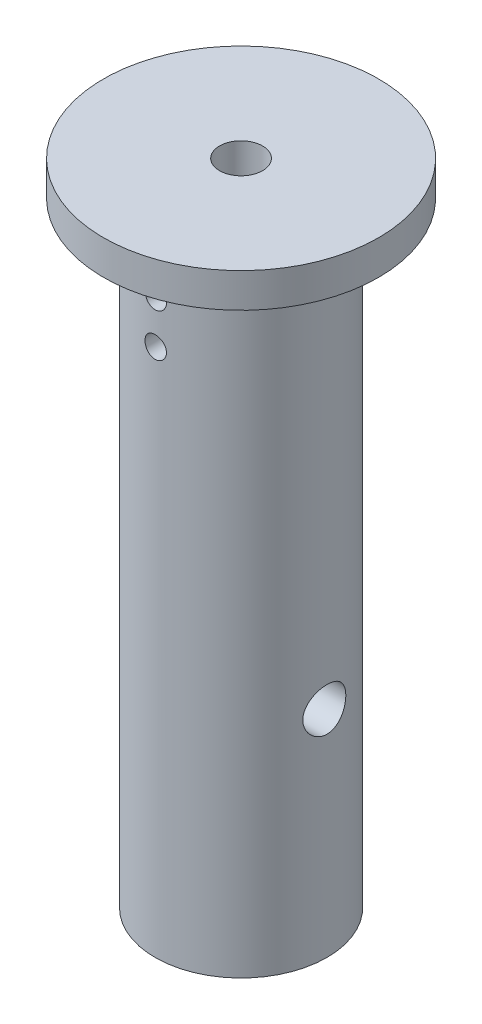
SolidWorks part; units mm, degrees
ref_plane "Front Plane" through (0, 0, 0) normal (0, 0, 1) x (1, 0, 0)
ref_plane "Top Plane" through (0, 0, 0) normal (0, 1, 0) x (1, 0, 0)
ref_plane "Right Plane" through (0, 0, 0) normal (1, 0, 0) x (0, 0, -1)
sketch "Sketch1" plane through (0, 0, 0) normal (0, 0, 1) x (1, 0, 0)
  line L0 (0, -45.5) -> (0, 42.4375) construction
  line L1 (2.5, 30) -> (2.5, 0)
  line L2 (2.5, 0) -> (0, 0)
  line L3 (0, 0) -> (0, -45.5)
  line L4 (0, -45.5) -> (10, -45.5)
  line L9 (10, -45.5) -> (10, 26)
  line L10 (10, 26) -> (16, 26)
  line L11 (16, 26) -> (16, 30)
  line L12 (16, 30) -> (2.5, 30)
  dimension "D1" = 30
  dimension "D3" = 32
  dimension "D4" = 5
  dimension "D5" = 20
  dimension "D6" = 4
  dimension "D7" = 75.5
revolve "Revolve1" add sketch "Sketch1" angle 360 about L0
hole_wizard "M3 Tapped Hole2" positions "Sketch2" profile "Sketch3" tap size "M3" standard "ISO"
sketch "Sketch2" plane through (0, -45.5, 0) normal (0, -1, 0) x (-1, 0, 0)
  line L1 (-3.5355, -3.5355) -> (3.5355, -3.5355)
  line L2 (-3.5355, -3.5355) -> (-3.5355, 3.5355)
  line L3 (-3.5355, 3.5355) -> (3.5355, 3.5355)
  line L4 (3.5355, -3.5355) -> (3.5355, 3.5355)
  line L5 (-3.5355, -3.5355) -> (3.5355, 3.5355) construction
  line L6 (-3.5355, 3.5355) -> (3.5355, -3.5355) construction
  line L7 (0, 0) -> (7.0711, -7.0711) construction
  circle A0 centre (0, 0) radius 10 construction
  point P0 (-3.5355, 3.5355)
  point P392 (-3.5355, -3.5355)
  point P395 (3.5355, -3.5355)
  point P398 (3.5355, 3.5355)
sketch "Sketch3" plane through (3.5355, -45.5, -3.5355) normal (1, 0, 0) x (0, 0, -1)
  line L0 (0, 0) -> (0, 8.2511)
  line L1 (0, 8.2511) -> (1.25, 7.5)
  line L2 (1.25, 7.5) -> (1.25, 0)
  line L5 (1.25, 0) -> (0, 0)
  line L10 (0, 8.2511) -> (-1.25, 7.5) construction
  line L11 (0, -6.35) -> (0, 107.95) construction
  dimension "Tap Drill Dia." = 2.5
  dimension "Tap Drill Depth" = 7.5
  dimension "Drill Angle" = 118
cosmetic thread "Hole Thread1" parameters "D1"=6, "D2"=3
cosmetic thread "Hole Thread4" parameters "D1"=6, "D2"=3
cosmetic thread "Hole Thread5" parameters "D1"=6, "D2"=3
cosmetic thread "Hole Thread6" parameters "D1"=6, "D2"=3
ref_plane "Plane1" through (-10, 0, 0) normal (-1, 0, 0) x (0, 0, 1)
sketch "Sketch4" plane through (-10, 0, 0) normal (-1, 0, 0) x (0, 0, 1)
  line L0 (-16, 26) -> (16, 26) construction
  line L1 (-3, -5.5) -> (3, -5.5)
  line L2 (-3, -5.5) -> (-3, 10.5)
  line L3 (-3, 10.5) -> (3, 10.5)
  line L4 (3, -5.5) -> (3, 10.5)
  line L5 (-3, -5.5) -> (3, 10.5) construction
  line L6 (-3, 10.5) -> (3, -5.5) construction
  arc A0 (-3, -5.5) -> (3, -5.5) centre (0, -5.5) ccw
  arc A1 (-3, 10.5) -> (3, 10.5) centre (0, 10.5) cw
  point P0 (0, 2.5)
  dimension "D1" = 6
  dimension "D2" = 16
  dimension "D3" = 31.5
extrude "Cut-Extrude1" cut sketch "Sketch4" against normal blind 3.5 contours L1 L4 L3 L2 | A1 L3 | L1 A0
hole_wizard "M3 Tapped Hole1" positions "Sketch7" profile "Sketch6" tap size "M3" standard "ISO"
sketch "Sketch7" plane through (0, 0, 0) normal (0, 0, 1) x (1, 0, 0)
  line L0 (-10, 26) -> (10, 26) construction
  point P0 (0, 21)
  point P2 (0, 16)
  dimension "D1" = 5
  dimension "D2" = 5
sketch "Sketch6" plane through (0, 21, 0) normal (1, 0, 0) x (0, 1, 0)
  line L0 (0, 0) -> (0, 16)
  line L1 (0, 16) -> (1.25, 16)
  line L2 (1.25, 16) -> (1.25, 0)
  line L5 (1.25, 0) -> (0, 0)
  line L11 (0, -6.35) -> (0, 107.95) construction
  dimension "Thru Tap Drill Dia." = 2.5
  dimension "Thru Tap Drill Depth" = 16
cosmetic thread "Hole Thread2" parameters "D2"=3
cosmetic thread "Hole Thread3" parameters "D2"=3
sketch "Sketch8" plane through (0, 0, 0) normal (1, 0, 0) x (0, 0, -1)
  line L0 (-10, -45.5) -> (10, -45.5) construction
  circle A0 centre (0, -20.5) radius 2.5
  dimension "D1" = 5
  dimension "D2" = 25
extrude "Cut-Extrude2" cut sketch "Sketch8" against normal through all both and the other way through all
